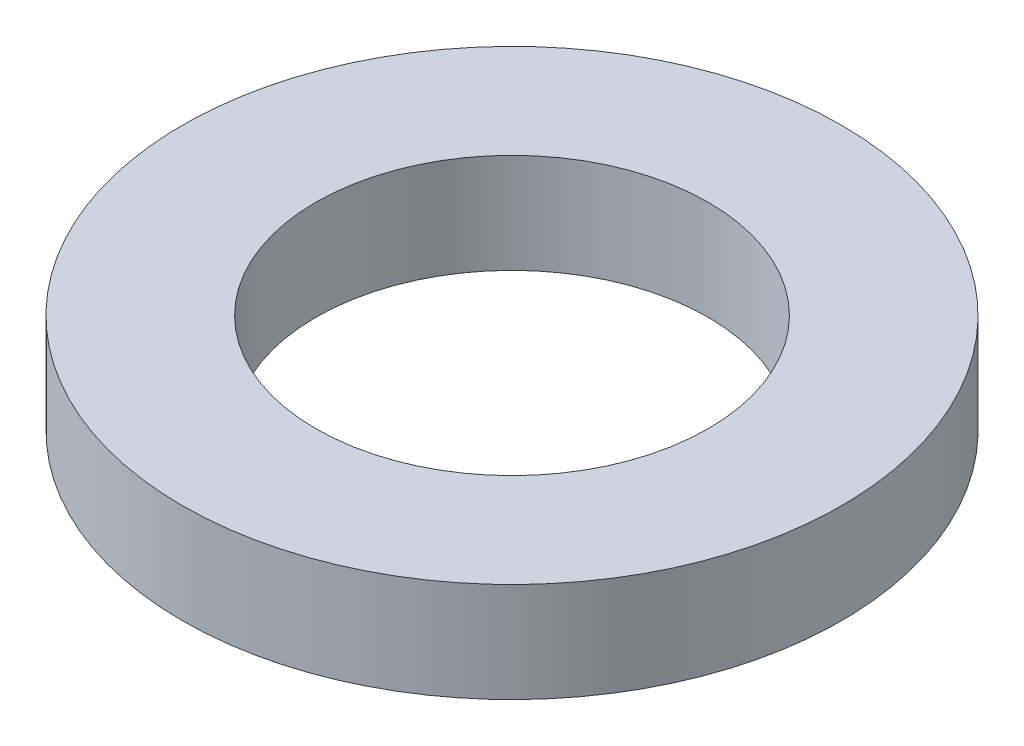
SolidWorks part; units mm, degrees
ref_plane "Front Plane" through (0, 0, 0) normal (0, 0, 1) x (1, 0, 0)
ref_plane "Top Plane" through (0, 0, 0) normal (0, 1, 0) x (1, 0, 0)
ref_plane "Right Plane" through (0, 0, 0) normal (1, 0, 0) x (0, 0, -1)
sketch "Sketch1" plane through (0, 0, 0) normal (0, 1, 0) x (1, 0, 0)
  circle A0 centre (0, 0) radius 4.2
  circle A1 centre (0, 0) radius 2.5
  dimension "D1" = 5
  dimension "D2" = 8.4
extrude "Boss-Extrude1" add sketch "Sketch1" along normal blind 1.27
